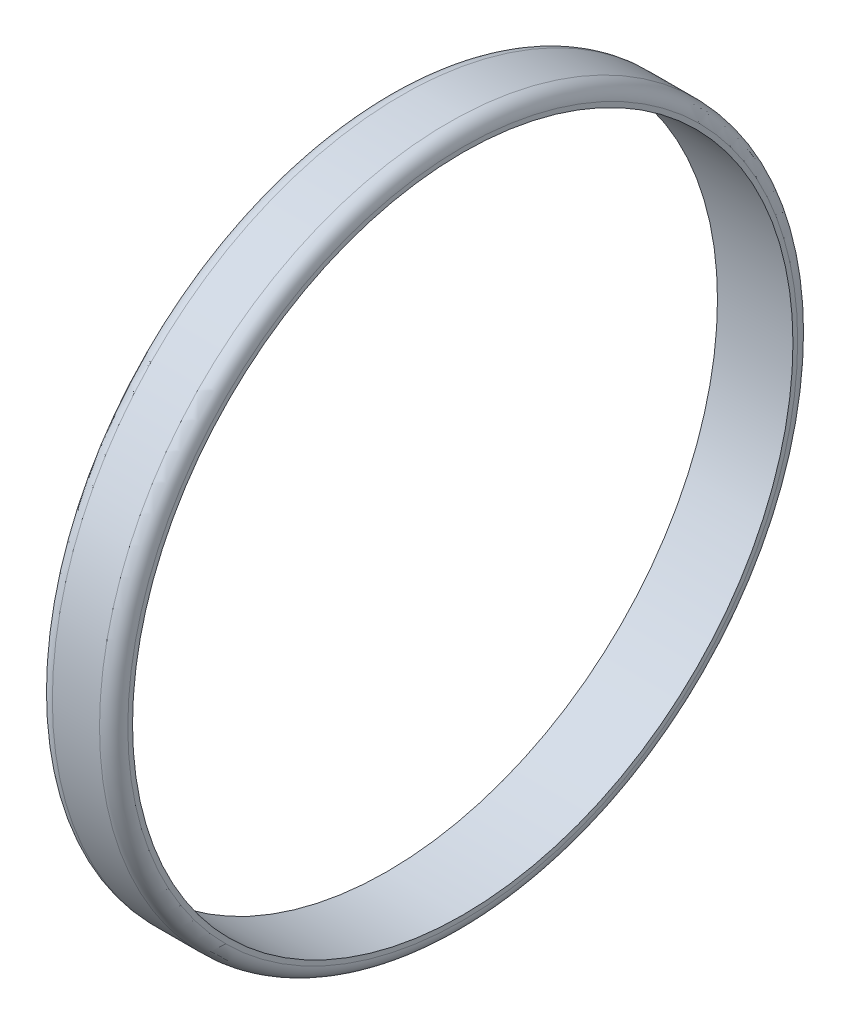
SolidWorks part; units mm, degrees
ref_plane "Front Plane" through (0, 0, 0) normal (1, 0, 0) x (0, 1, 0)
ref_plane "Top Plane" through (0, 0, 0) normal (0, 0, 1) x (0, 1, 0)
ref_plane "Right Plane" through (0, 0, 0) normal (0, 1, 0) x (-1, 0, 0)
sketch "Sketch1" plane through (0, 0, 0) normal (1, 0, 0) x (0, 1, 0)
  circle A0 centre (0, 0) radius 37
  dimension "D1" = 74
extrude "Boss-Extrude1" add sketch "Sketch1" along normal blind 8 contours A0
fillet "Fillet1" radius 1.5 2 edges at (0, 0, -37) (8, 0, -37)
sketch "Sketch2" plane through (8, 0, 0) normal (1, 0, 0) x (0, 1, 0)
  circle A0 centre (0, 0) radius 35
  dimension "D1" = 70
extrude "Cut-Extrude1" cut sketch "Sketch2" against normal through all
